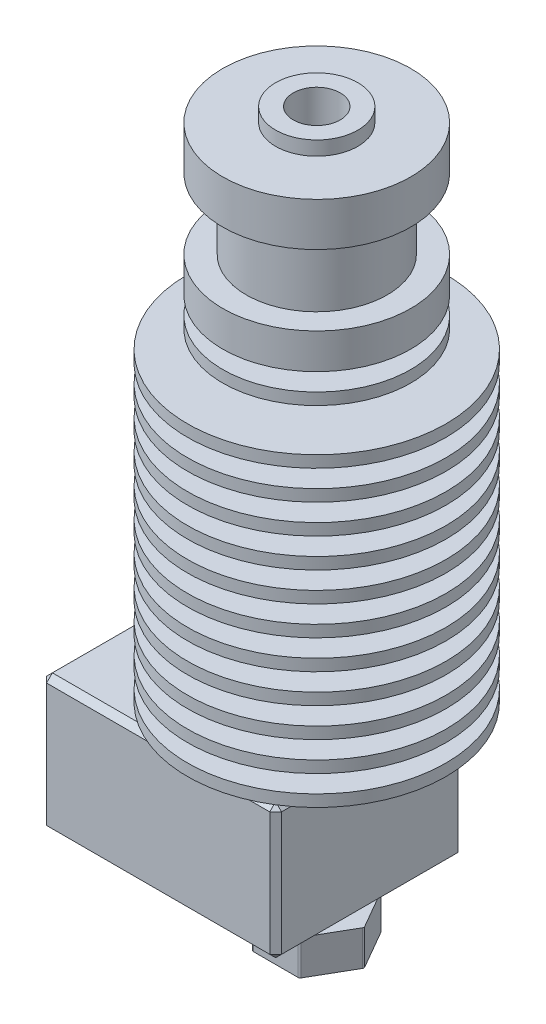
SolidWorks part; units mm, degrees
ref_plane "Front Plane" through (0, 0, 0) normal (0, 0, 1) x (1, 0, 0)
ref_plane "Top Plane" through (0, 0, 0) normal (0, 1, 0) x (1, 0, 0)
ref_plane "Right Plane" through (0, 0, 0) normal (1, 0, 0) x (0, 0, -1)
sketch "Sketch1" plane through (0, 0, 0) normal (0, 0, 1) x (1, 0, 0)
  line L0 (0, 0) -> (-8, 0)
  line L1 (-8, 0) -> (-8, -3.7)
  line L2 (-8, -3.7) -> (-6, -3.7)
  line L3 (-6, -3.7) -> (-6, -9.7)
  line L4 (-6, -9.7) -> (-8, -9.7)
  line L5 (-8, -9.7) -> (-8, -12.7)
  line L6 (-8, -12.7) -> (-4, -12.7)
  line L7 (-4, -12.7) -> (-4, -14.2)
  line L8 (-4, -14.2) -> (-8, -14.2)
  line L9 (-8, -14.2) -> (-8, -15.2)
  line L10 (-8, -15.2) -> (-4, -15.2)
  line L11 (-4, -15.2) -> (-4, -16.7)
  line L12 (-4, -16.7) -> (-11, -16.7)
  line L13 (-11, -16.7) -> (-11, -17.7)
  line L14 (-11, -17.7) -> (-3, -17.7)
  line L15 (-3, -17.7) -> (-3, -19.2)
  line L16 (-3, -19.2) -> (-11, -19.2)
  line L17 (-11, -19.2) -> (-11, -20.2)
  line L18 (-11, -20.2) -> (-3, -20.2)
  line L19 (-3, -20.2) -> (-3, -21.7)
  line L20 (-3, -21.7) -> (-11, -21.7)
  line L21 (-11, -21.7) -> (-11, -22.7)
  line L22 (-11, -22.7) -> (-3, -22.7)
  line L23 (-3, -22.7) -> (-3, -24.2)
  line L24 (-3, -24.2) -> (-11, -24.2)
  line L25 (-11, -24.2) -> (-11, -25.2)
  line L26 (-11, -25.2) -> (-3, -25.2)
  line L27 (-3, -25.2) -> (-3, -26.7)
  line L28 (-3, -26.7) -> (-11, -26.7)
  line L29 (-11, -26.7) -> (-11, -27.7)
  line L30 (-11, -27.7) -> (-3, -27.7)
  line L31 (-3, -27.7) -> (-3, -29.2)
  line L32 (-3, -29.2) -> (-11, -29.2)
  line L33 (-11, -29.2) -> (-11, -30.2)
  line L34 (-11, -30.2) -> (-3, -30.2)
  line L35 (-3, -30.2) -> (-3, -31.7)
  line L36 (-3, -31.7) -> (-11, -31.7)
  line L37 (-11, -31.7) -> (-11, -32.7)
  line L38 (-11, -32.7) -> (-3, -32.7)
  line L39 (-3, -32.7) -> (-3, -34.2)
  line L40 (-3, -34.2) -> (-11, -34.2)
  line L41 (-11, -34.2) -> (-11, -35.2)
  line L42 (-11, -35.2) -> (-3, -35.2)
  line L43 (-3, -35.2) -> (-3, -36.7)
  line L44 (-3, -36.7) -> (-11, -36.7)
  line L45 (-11, -36.7) -> (-11, -37.7)
  line L46 (-11, -37.7) -> (-3, -37.7)
  line L47 (-3, -37.7) -> (-3, -39.2)
  line L48 (-3, -39.2) -> (-11, -39.2)
  line L49 (-11, -39.2) -> (-11, -40.2)
  line L50 (-11, -40.2) -> (-3, -40.2)
  line L51 (55, 0) -> (-55, 0) construction
  line L52 (0, -55) -> (0, 55) construction
  line L53 (-3, -40.2) -> (-3, -41.7)
  line L54 (-3, -41.7) -> (-11, -41.7)
  line L55 (-11, -41.7) -> (-11, -42.7)
  line L56 (-11, -42.7) -> (0, -42.7)
  line L57 (0, 0) -> (0, -42.7) construction
  line L58 (0, 0) -> (0, -42.7)
  dimension "D1" = 3.7
  dimension "D2" = 16
  dimension "D3" = 6
  dimension "D4" = 12
  dimension "D5" = 3
  dimension "D6" = 16
  dimension "D7" = 16.7
  dimension "D8" = 16
  dimension "D9" = 22
  dimension "D10" = 42.7
  dimension "D11" = 8
  dimension "D12" = 6
revolve "Revolve1" add sketch "Sketch1" angle 360 about L57
sketch "Sketch2" plane through (0, 0, 0) normal (0, 1, 0) x (1, 0, 0)
  circle A0 centre (0, 0) radius 3.5
  dimension "D1" = 7
extrude "Boss-Extrude1" add sketch "Sketch2" along normal blind 1.2
sketch "Sketch3" plane through (0, 1.2, 0) normal (0, 1, 0) x (1, 0, 0)
  circle A0 centre (0, 0) radius 0.875
  dimension "D1" = 1.75
extrude "Cut-Extrude1" cut sketch "Sketch3" against normal through all
sketch "Sketch10" plane through (0, 1.2, 0) normal (0, 1, 0) x (1, 0, 0)
  circle A0 centre (0, 0) radius 2
  dimension "D1" = 4
extrude "Cut-Extrude4" cut sketch "Sketch10" against normal offset from surface (33.9 mm away) 10 up to face at (-0.875, -42.7, 0)
sketch "Sketch5" plane through (0, 0, 0) normal (0, 0, 1) x (1, 0, 0)
  line L0 (0, -42.7) -> (-2.5, -42.7)
  line L1 (-2.5, -42.7) -> (-2.5, -57.3)
  line L2 (8, 0) -> (-8, 0) construction
  line L3 (0, -42.7) -> (0, -62.3)
  line L4 (-2.5, -57.3) -> (-5, -57.3)
  line L5 (-5, -57.3) -> (-5, -60.3)
  line L6 (-5, -60.3) -> (-1.7154, -60.3)
  line L7 (-1.7154, -60.3) -> (-0.315, -62.3)
  line L8 (-0.315, -62.3) -> (0, -62.3)
  line L9 (0, -62.3) -> (0, -42.7) construction
  line L10 (-11, -42.7) -> (11, -42.7) construction
  line L11 (0, -12.1) -> (0, 12.1) construction
  dimension "D1" = 5
  dimension "D3" = 10
  dimension "D2" = 3
  dimension "D5" = 62.3
  dimension "D6" = 125
  dimension "D4" = 2
  dimension "D7" = 0.315
revolve "Revolve2" add sketch "Sketch5" angle 360 about L9
sketch "Sketch6" plane through (0, -60.3, 0) normal (0, -1, 0) x (1, 0, 0)
  line L1 (2.0207, 3.5) -> (-2.0207, 3.5)
  line L2 (-2.0207, 3.5) -> (-4.0415, 0)
  line L3 (-4.0415, 0) -> (-2.0207, -3.5)
  line L4 (-2.0207, -3.5) -> (2.0207, -3.5)
  line L5 (2.0207, -3.5) -> (4.0415, 0)
  line L6 (4.0415, 0) -> (2.0207, 3.5)
  circle A0 centre (0, 0) radius 3.5 construction
  dimension "D1" = 7
extrude "Cut-Extrude2" cut sketch "Sketch6" against normal up to surface (3 mm away) flip side to cut up to face at (0, -57.3, -5)
fillet "Fillet1" radius 0.2 6 edges at (-2.0207, -58.8, 3.5) (2.0207, -58.8, -3.5) (-2.0207, -58.8, -3.5) (-4.0415, -58.8, 0) (4.0415, -58.8, 0) (2.0207, -58.8, 3.5)
sketch "Sketch7" plane through (0, -57.3, 0) normal (0, 1, 0) x (1, 0, 0)
  line L0 (0, 0) -> (-5.5, 0) construction
  line L1 (-15.5, 8) -> (4.5, 8)
  line L2 (-15.5, 8) -> (-15.5, -8)
  line L3 (-15.5, -8) -> (4.5, -8)
  line L4 (4.5, 8) -> (4.5, -8)
  line L5 (-15.5, 8) -> (4.5, -8) construction
  line L6 (-15.5, -8) -> (4.5, 8) construction
  point P0 (-5.5, 0)
  dimension "D1" = 16
  dimension "D2" = 20
  dimension "D3" = 4.5
extrude "Boss-Extrude2" add sketch "Sketch7" along normal blind 11.5 from offset 1.5
chamfer "Chamfer2" distance 0.5 angle 45 12 edges at (-15.5, -50.05, -8) (4.5, -50.05, -8) (4.5, -50.05, 8) (-15.5, -50.05, 8) (4.5, -55.8, 0) (4.5, -44.3, 0) (-5.5, -44.3, 8) (-5.5, -55.8, 8) (-15.5, -55.8, 0) (-5.5, -44.3, -8) (-5.5, -55.8, -8) (-15.5, -44.3, 0)
sketch "Sketch8" plane through (0, -62.3, 0) normal (0, -1, 0) x (1, 0, 0)
  circle A0 centre (0, 0) radius 0.2
  dimension "D1" = 0.4
extrude "Cut-Extrude3" cut sketch "Sketch8" against normal through all
sketch "Sketch9" plane through (0, 0, 0) normal (0, 0, 1) x (1, 0, 0)
  line L1 (-1.4, -42.7) -> (-3, -42.7)
  line L2 (-1.4, -42.7) -> (-1.4, -44.3)
  line L3 (-1.4, -44.3) -> (-3, -44.3)
  line L4 (-3, -42.7) -> (-3, -44.3)
  line L5 (-1.4, -42.7) -> (-3, -44.3) construction
  line L6 (-1.4, -44.3) -> (-3, -42.7) construction
  line L9 (0, -12.1) -> (0, 12.1) construction
  line L10 (0, -42.7) -> (0, -44.3) construction
  line L12 (2.5, -42.7) -> (-2.5, -42.7) construction
  line L13 (-15, -44.3) -> (4, -44.3) construction
  point P0 (-2.2, -43.5)
  dimension "D1" = 1.4
revolve "Cut-Revolve1" cut sketch "Sketch9" angle 360 about L10
equation "\"D7@Sketch5\"=0.63 / 2"
